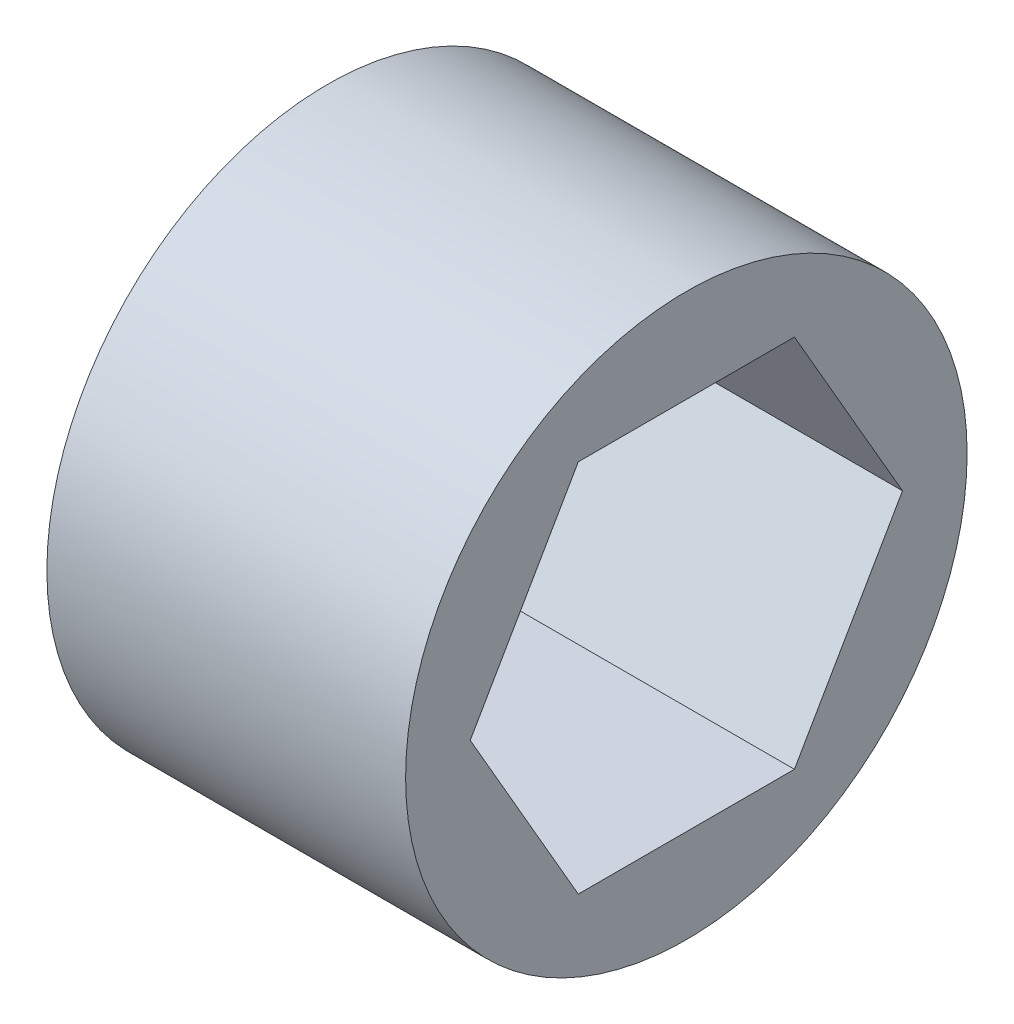
SolidWorks part; units mm, degrees
material "PET"
ref_plane "Front" through (0, 0, 0) normal (0, 0, 1) x (1, 0, 0)
ref_plane "Top" through (0, 0, 0) normal (0, 1, 0) x (1, 0, 0)
ref_plane "Right" through (0, 0, 0) normal (1, 0, 0) x (0, 0, -1)
sketch "Sketch1" plane through (0, 0, 0) normal (1, 0, 0) x (0, 0, -1)
  line L1 (7.3323, 0) -> (3.6662, 6.35)
  line L2 (3.6662, 6.35) -> (-3.6662, 6.35)
  line L3 (-3.6662, 6.35) -> (-7.3323, 0)
  line L4 (-7.3323, 0) -> (-3.6662, -6.35)
  line L5 (-3.6662, -6.35) -> (3.6662, -6.35)
  line L6 (3.6662, -6.35) -> (7.3323, 0)
  circle A0 centre (0, 0) radius 6.35 construction
  circle A1 centre (0, 0) radius 9.525
  dimension "D2" = 19.05
  dimension "D1" = 12.7
extrude "Boss-Extrude1" add sketch "Sketch1" along normal mid plane 12.17
